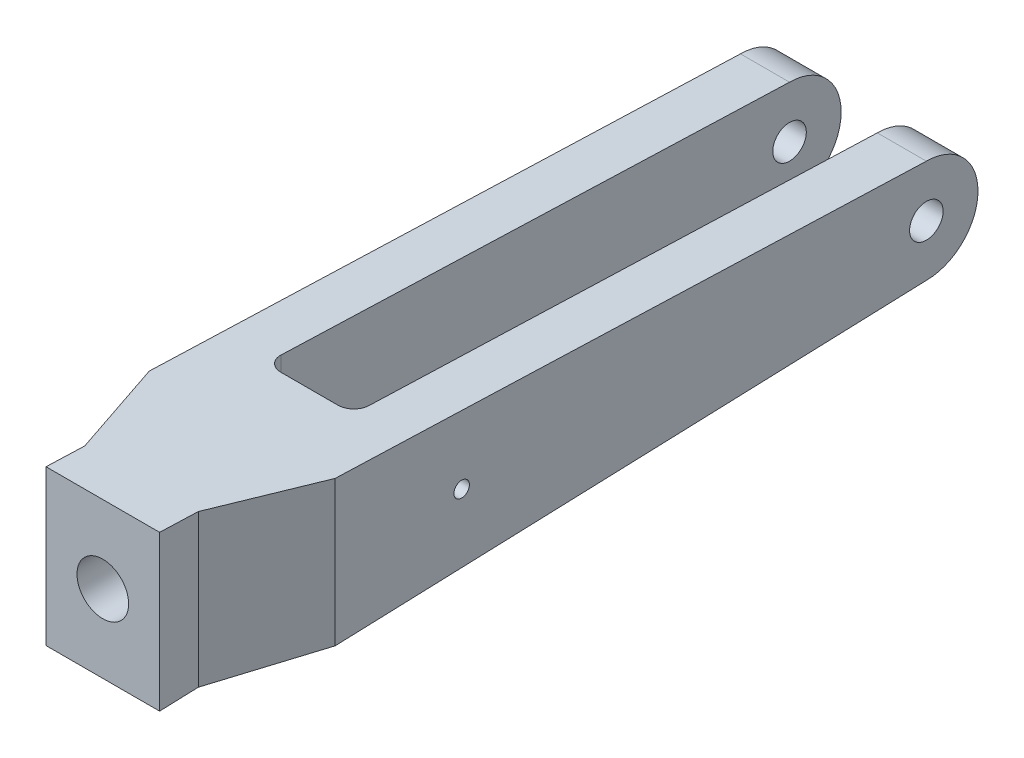
SolidWorks part; units mm, degrees
ref_plane "Front Plane" through (0, 0, 0) normal (0, 0, 1) x (1, 0, 0)
ref_plane "Top Plane" through (0, 0, 0) normal (0, 1, 0) x (1, 0, 0)
ref_plane "Right Plane" through (0, 0, 0) normal (1, 0, 0) x (0, 0, -1)
sketch "Sketch1" plane through (0, 0, 0) normal (0, 1, 0) x (1, 0, 0)
  line L0 (-7.0013, 151.499) -> (2.4987, 151.499)
  line L1 (-0.0013, -0.001) -> (21.9987, -0.001)
  line L5 (2.4987, 151.499) -> (2.4987, 39.999)
  line L6 (2.4987, 39.999) -> (19.4987, 39.999)
  line L7 (19.4987, 39.999) -> (19.4987, 151.499)
  line L8 (19.4987, 151.499) -> (28.9987, 151.499)
  line L9 (-7.0013, 26.999) -> (28.9987, 26.999) construction
  line L10 (-0.0013, 7.499) -> (28.9987, 7.499) construction
  line L11 (-7.0013, 26.999) -> (-7.0013, 151.499)
  line L13 (-0.0013, -0.001) -> (-0.0013, 7.499)
  line L14 (-0.0013, 7.499) -> (-7.0013, 26.999)
  line L15 (21.9987, -0.001) -> (21.9987, 7.499)
  line L16 (21.9987, 7.499) -> (28.9987, 26.999)
  line L17 (28.9987, 26.999) -> (28.9987, 151.499)
  dimension "D3" = 17
  dimension "D4" = 9.5
  dimension "D5" = 9.5
  dimension "D6" = 40
  dimension "D7" = 27
  dimension "D8" = 7.5
extrude "Boss-Extrude1" add sketch "Sketch1" along normal blind 30
sketch "Sketch3" plane through (28.9987, 0, 0) normal (1, 0, 0) x (0, 0, -1)
  line L1 (-0.001, 30) -> (-0.001, 0) construction
  line L5 (-0.001, 30) -> (141.499, 25)
  line L6 (-0.001, 0) -> (141.499, 5)
  line L7 (-0.001, 30) -> (151.499, 30)
  line L8 (-0.001, 30) -> (-0.001, 0)
  line L9 (-0.001, 0) -> (151.499, 0)
  line L10 (151.499, 30) -> (151.499, 0)
  circle A0 centre (141.499, 15) radius 3.25
  circle A1 centre (51.499, 15) radius 1.5
  arc A2 (141.499, 5) -> (141.499, 25) centre (141.499, 15) ccw
  line M7 (26.999, 0) -> (151.499, 0)
  line M8 (151.499, 0) -> (151.499, 30)
  line M9 (151.499, 30) -> (26.999, 30)
  line M10 (26.999, 30) -> (26.999, 0)
  dimension "D3" = 20
  dimension "D4" = 6.5
  dimension "D5" = 3
extrude "Cut-Extrude2" cut sketch "Sketch3" against normal blind 100 contours A2 L10 L5 M9 M10 | A2 L6 M10 M7 M8 | L7 L5 M10 | L6 L9 M10 | A1 | A0
fillet "Fillet1" radius 3 2 edges at (2.4987, 15, -39.999) (19.4987, 15, -39.999)
sketch "Sketch6" plane through (0, 0, 0.001) normal (0, 0, 1) x (1, 0, 0)
  line L0 (10.9987, 30) -> (10.9987, 0) construction
  line L1 (-0.0013, 30) -> (21.9987, 30) construction
  line L2 (-0.0013, 0) -> (21.9987, 0) construction
  line L3 (21.9987, 15) -> (-0.0013, 15) construction
  line L4 (21.9987, 29.735) -> (21.9987, 0.265) construction
  line L5 (-0.0013, 30) -> (-0.0013, 0) construction
  circle A0 centre (10.9987, 15) radius 5
  dimension "D1" = 10
extrude "Cut-Extrude3" cut sketch "Sketch6" against normal blind 30 contours A0
